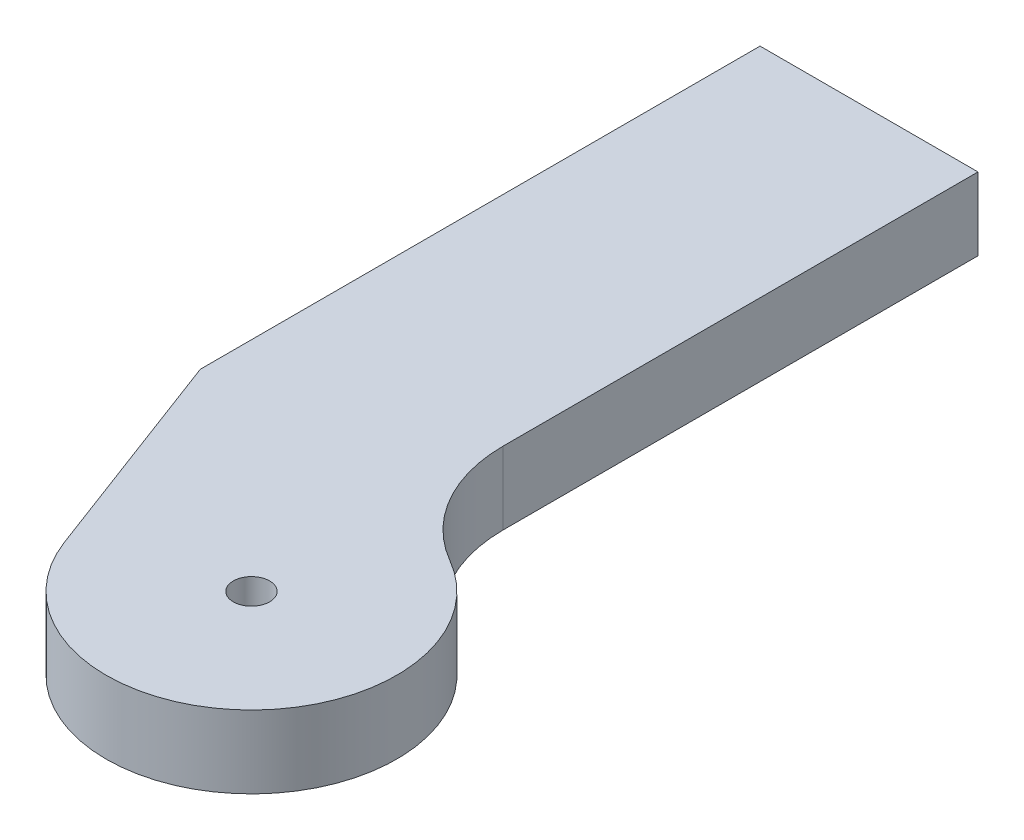
SolidWorks part; units mm, degrees
ref_plane "Front" through (0, 0, 0) normal (0, 0, 1) x (1, 0, 0)
ref_plane "Top" through (0, 0, 0) normal (0, 1, 0) x (1, 0, 0)
ref_plane "Right" through (0, 0, 0) normal (1, 0, 0) x (0, 0, -1)
sketch "Sketch1" plane through (0, 0, 0) normal (0, 1, 0) x (1, 0, 0)
  line L0 (-9.3603, -3.5193) -> (-15, 11.4807)
  line L1 (0, 0) -> (0, 50)
  line L2 (-15, 11.4807) -> (-15, 50)
  line L3 (-15, 50) -> (0, 50)
  circle A0 centre (0, 0) radius 10
  point P5 (-12.5, 16.602)
  point P8 (-12.5, 0)
  point P9 (-19.2108, 17.9944)
  dimension "D1" = 20
  dimension "D2" = 15
  dimension "D3" = 15
  dimension "D4" = 50
extrude "Boss-Extrude1" add sketch "Sketch1" along normal blind 5
fillet "Fillet1" radius 10 1 edges at (0, 2.5, -10)
sketch "Sketch2" plane through (0, 5, 0) normal (0, 1, 0) x (1, 0, 0)
  circle A0 centre (0, 0) radius 1.25
  point P2 (0, 0)
  dimension "D1" = 2.5
extrude "Cut-Extrude1" cut sketch "Sketch2" against normal through all
